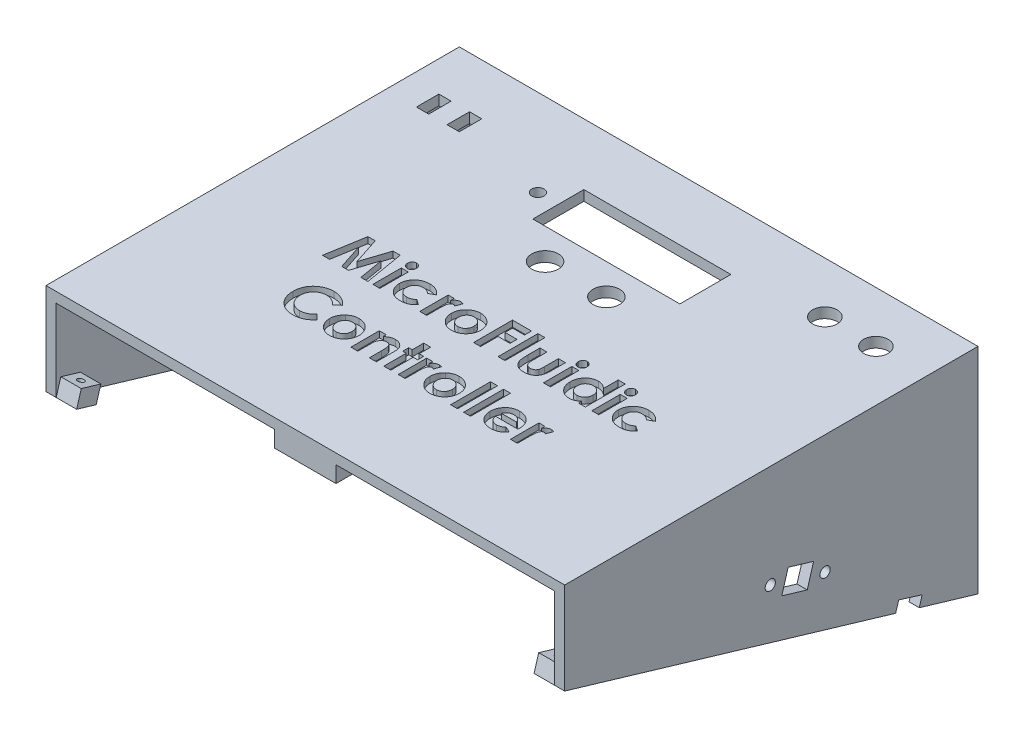
SolidWorks part; units mm, degrees
ref_plane "Front Plane" through (0, 0, 0) normal (0, 0, 1) x (1, 0, 0)
ref_plane "Top Plane" through (0, 0, 0) normal (0, 1, 0) x (1, 0, 0)
ref_plane "Right Plane" through (0, 0, 0) normal (1, 0, 0) x (0, 0, -1)
sketch "Sketch1" plane through (0, 0, 0) normal (0, 1, 0) x (1, 0, 0)
  line L1 (-127, -101.2) -> (127, -101.2)
  line L2 (-127, -101.2) -> (-127, 101.2)
  line L3 (-127, 101.2) -> (127, 101.2)
  line L4 (127, -101.2) -> (127, 101.2)
  line L5 (-127, -101.2) -> (127, 101.2) construction
  line L6 (-127, 101.2) -> (127, -101.2) construction
  point P0 (0, 0)
  dimension "D1" = 254
  dimension "D2" = 202.4
extrude "Boss-Extrude1" add sketch "Sketch1" along normal blind 5
sketch "Sketch2" plane through (0, 5, 0) normal (0, 1, 0) x (1, 0, 0)
  line L0 (0, 101.2) -> (0, -101.2) construction
  line L1 (127, 101.2) -> (-127, 101.2) construction
  line L2 (-127, -101.2) -> (127, -101.2) construction
  line L3 (-127, 0) -> (127, 0) construction
  line L4 (-127, 101.2) -> (-127, -101.2) construction
  line L5 (127, -101.2) -> (127, 101.2) construction
  line L7 (-36, 46.2) -> (36, 46.2)
  line L8 (-36, 46.2) -> (-36, 71.2)
  line L9 (-36, 71.2) -> (36, 71.2)
  line L10 (36, 46.2) -> (36, 71.2)
  line L11 (-36, 46.2) -> (36, 71.2) construction
  line L12 (-36, 71.2) -> (36, 46.2) construction
  point P12 (0, 58.7)
  dimension "D1" = 25
  dimension "D2" = 72
  dimension "D3" = 30
extrude "Cut-Extrude1" cut sketch "Sketch2" against normal blind 10
sketch "Sketch3" plane through (0, 5, 0) normal (0, 1, 0) x (1, 0, 0)
  line L0 (127, 101.2) -> (-127, 101.2) construction
  line L1 (127, -101.2) -> (127, 101.2) construction
  circle A0 centre (77, 76.2) radius 6
  circle A1 centre (102, 76.2) radius 6
  dimension "D1" = 12
  dimension "D2" = 25
  dimension "D3" = 50
  dimension "D4" = 2
extrude "Cut-Extrude2" cut sketch "Sketch3" against normal blind 10
sketch "Sketch4" plane through (0, 5, 0) normal (0, 1, 0) x (1, 0, 0)
  line L0 (127, 101.2) -> (-127, 101.2) construction
  line L1 (-112, 76.2) -> (-106, 76.2)
  line L2 (-112, 76.2) -> (-112, 65.2)
  line L3 (-112, 65.2) -> (-106, 65.2)
  line L4 (-106, 76.2) -> (-106, 65.2)
  line L5 (-112, 76.2) -> (-106, 65.2) construction
  line L6 (-112, 65.2) -> (-106, 76.2) construction
  line L7 (-127, 101.2) -> (-127, -101.2) construction
  line L8 (-91, 76.2) -> (-91, 65.2)
  line L9 (-97, 76.2) -> (-91, 76.2)
  line L10 (-97, 76.2) -> (-97, 65.2)
  line L11 (-97, 65.2) -> (-91, 65.2)
  point P0 (-109, 70.7)
  dimension "D1" = 11
  dimension "D2" = 6
  dimension "D3" = 25
  dimension "D4" = 15
  dimension "D5" = 2
extrude "Cut-Extrude3" cut sketch "Sketch4" against normal blind 10
sketch "Sketch5" plane through (0, 5, 0) normal (0, 1, 0) x (1, 0, 0)
  line L0 (0, -2.75) -> (0, 2.75) construction
  line L1 (-36, 46.2) -> (36, 46.2) construction
  line L2 (-36, 71.2) -> (-36, 46.2) construction
  circle A0 centre (-15, 31.2) radius 6.5
  circle A1 centre (15, 31.2) radius 6.5
  circle A2 centre (-46, 58.7) radius 3
  point P12 (-36, 58.7)
  dimension "D1" = 13
  dimension "D2" = 13
  dimension "D8" = 6
  dimension "D3" = 30
  dimension "D4" = 15
  dimension "D5" = 15
  dimension "D6" = 0
  dimension "D7" = 10
extrude "Cut-Extrude4" cut sketch "Sketch5" against normal blind 10
sketch "Sketch6" plane through (0, 5, 0) normal (0, 1, 0) x (1, 0, 0)
  text T0 "MicroFluidic \r\n Controller" font "Century Gothic" height in points 72
extrude "Cut-Extrude5" cut sketch "Sketch6" against normal blind 3
sketch "Sketch7" plane through (0, 0, 0) normal (0, -1, 0) x (1, 0, 0)
  line L0 (-127, 101.2) -> (127, 101.2) construction
  line L1 (15, 61.2) -> (-15, 61.2)
  line L2 (15, 61.2) -> (15, 101.2)
  line L3 (15, 101.2) -> (-15, 101.2)
  line L4 (-15, 61.2) -> (-15, 101.2)
  line L5 (15, 61.2) -> (-15, 101.2) construction
  line L6 (15, 101.2) -> (-15, 61.2) construction
  line L7 (0, -2.75) -> (0, 2.75) construction
  line L8 (127, -101.2) -> (-127, -101.2) construction
  line L9 (15, -81.2) -> (-15, -81.2)
  line L10 (15, -81.2) -> (15, -101.2)
  line L11 (15, -101.2) -> (-15, -101.2)
  line L12 (-15, -81.2) -> (-15, -101.2)
  line L13 (15, -81.2) -> (-15, -101.2) construction
  line L14 (15, -101.2) -> (-15, -81.2) construction
  point P0 (0, 81.2)
  point P9 (0, -91.2)
  dimension "D1" = 40
  dimension "D2" = 30
  dimension "D3" = 15
  dimension "D4" = 20
  dimension "D5" = 30
extrude "Boss-Extrude2" add sketch "Sketch7" along normal blind 8
sketch "Sketch9" plane through (15, 0, 0) normal (1, 0, 0) x (0, 0, -1)
  line L0 (101.2, -8) -> (81.2, -8) construction
  line L1 (-101.2, -8) -> (-101.2, 0) construction
  circle A0 centre (89.5846, -4) radius 1.75
  circle A1 centre (-91.2, -4) radius 1.75
  circle A2 centre (-71.2, -4) radius 1.75
  dimension "D1" = 3.5
  dimension "D2" = 4
  dimension "D3" = 3.5
  dimension "D4" = 3.5
  dimension "D5" = 20
  dimension "D6" = 10
extrude "Cut-Extrude6" cut sketch "Sketch9" against normal blind 40
sketch "Sketch10" plane through (127, 0, 0) normal (1, 0, 0) x (0, 0, -1)
  line L0 (101.2, 0) -> (101.2, -100)
  line L1 (101.2, -100) -> (-101.2, -40)
  line L2 (-101.2, -40) -> (-101.2, 0)
  line L3 (-101.2, 0) -> (101.2, 0)
  dimension "D1" = 100
  dimension "D2" = 40
extrude "Boss-Extrude3" add sketch "Sketch10" against normal blind 5
sketch "Sketch11" plane through (-127, 0, 0) normal (-1, 0, 0) x (0, 0, 1)
  line L0 (101.2, 0) -> (101.2, -40)
  line L1 (101.2, -40) -> (-101.2, -100)
  line L2 (-101.2, -100) -> (-101.2, 0)
  line L3 (-101.2, 0) -> (101.2, 0)
  dimension "D1" = 40
  dimension "D2" = 100
extrude "Boss-Extrude4" add sketch "Sketch11" against normal blind 5
sketch "Sketch12" plane through (0, -64.3454, 19.0747) normal (0, -0.9588, 0.2842) x (1, 0, 0)
  line L0 (0, -130.3205) -> (0, 193.6602) construction
  line L1 (-112, 85.6578) -> (-112, 75.6578)
  line L2 (122, -125.4482) -> (112, -125.4482)
  line L3 (122, -125.4482) -> (122, -115.4482)
  line L4 (122, -115.4482) -> (112, -115.4482)
  line L5 (112, -125.4482) -> (112, -115.4482)
  line L6 (122, 85.6578) -> (112, 85.6578)
  line L7 (122, 85.6578) -> (122, 75.6578)
  line L8 (122, 75.6578) -> (112, 75.6578)
  line L9 (112, 85.6578) -> (112, 75.6578)
  line L10 (-122, 85.6578) -> (-112, 85.6578)
  line L11 (-122, 85.6578) -> (-122, 75.6578)
  line L12 (-122, 75.6578) -> (-112, 75.6578)
  line L13 (-122, -115.4482) -> (-112, -115.4482)
  line L14 (-112, -125.4482) -> (-112, -115.4482)
  line L15 (-122, -125.4482) -> (-112, -125.4482)
  line L16 (-122, -125.4482) -> (-122, -115.4482)
  circle A0 centre (117, -120.4482) radius 1.6
  circle A1 centre (117, 80.6578) radius 1.6
  circle A2 centre (-117, 80.6578) radius 1.6
  circle A3 centre (-117, -120.4482) radius 1.6
  dimension "D5" = 3.2
  dimension "D6" = 3.2
  dimension "D1" = 10
  dimension "D2" = 10
  dimension "D3" = 10
  dimension "D4" = 10
extrude "Boss-Extrude5" add sketch "Sketch12" against normal blind 8
sketch "Sketch13" plane through (127, 0, 0) normal (1, 0, 0) x (0, 0, -1)
  line L0 (60.8758, -88.0462) -> (62.3935, -83.136)
  line L1 (-101.2, -40) -> (101.2, -100) construction
  line L2 (62.3935, -83.136) -> (73.8583, -86.6797)
  line L3 (73.8583, -86.6797) -> (72.4372, -91.4735)
  line L4 (72.4372, -91.4735) -> (60.8758, -88.0462)
  line L5 (5.1093, -52.7646) -> (17.5732, -56.4594)
  line L6 (5.1093, -52.7646) -> (8.2357, -42.2182)
  line L7 (17.5732, -56.4594) -> (20.6996, -45.913)
  line L8 (8.2357, -42.2182) -> (20.6996, -45.913)
  circle A0 centre (26.3271, -53.3178) radius 2.5
  circle A1 centre (-0.5182, -45.3598) radius 2.5
  dimension "D6" = 5
  dimension "D7" = 5
  dimension "D1" = 12
  dimension "D2" = 5
  dimension "D3" = 30
  dimension "D4" = 11
  dimension "D5" = 13
  dimension "D8" = 7.5
  dimension "D9" = 7.5
extrude "Cut-Extrude7" cut sketch "Sketch13" against normal blind 10
